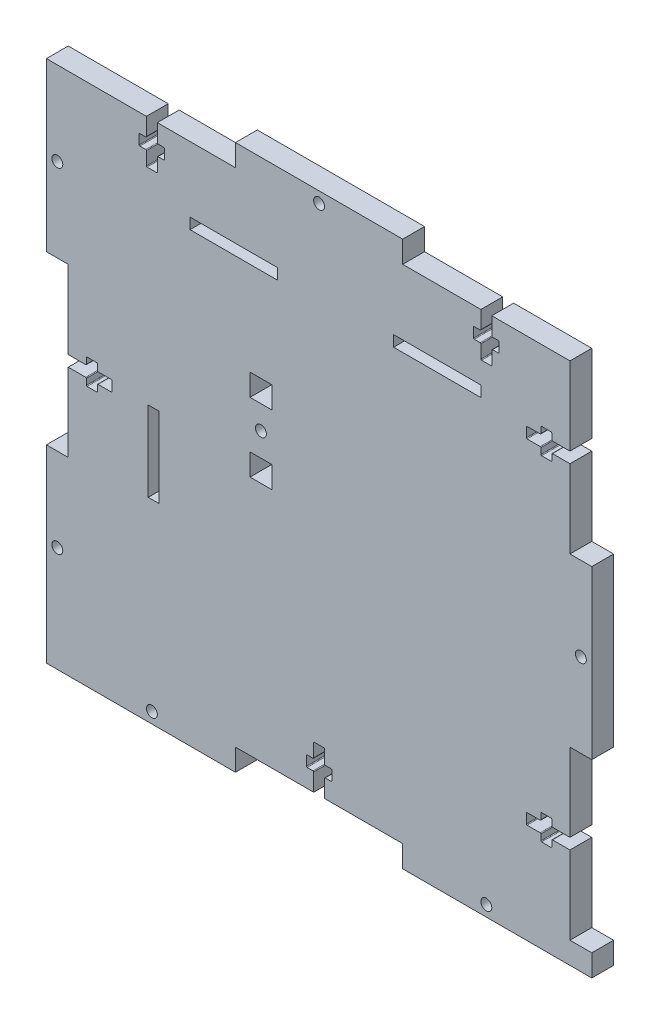
SolidWorks part; units mm, degrees
ref_plane "Front Plane" through (0, 0, 0) normal (0, 0, 1) x (1, 0, 0)
ref_plane "Top Plane" through (0, 0, 0) normal (0, 1, 0) x (1, 0, 0)
ref_plane "Right Plane" through (0, 0, 0) normal (1, 0, 0) x (0, 0, -1)
sketch "Sketch1" plane through (0, 0, 0) normal (0, 0, 1) x (1, 0, 0)
  line L0 (-69, 69) -> (-23, 69)
  line L5 (-75, -75) -> (75, -75) construction
  line L6 (-75, -75) -> (-75, 75) construction
  line L7 (-75, 75) -> (75, 75) construction
  line L8 (75, -75) -> (75, 75) construction
  line L9 (75, 23) -> (69, 23)
  line L10 (69, -23) -> (75, -23)
  line L11 (-69, -69) -> (69, -69) construction
  line L12 (-69, -69) -> (-69, 69) construction
  line L13 (-69, 69) -> (69, 69) construction
  line L14 (69, -69) -> (69, 69) construction
  line L15 (-69, -69) -> (69, 69) construction
  line L16 (69, -69) -> (69, -23)
  line L17 (-23, 69) -> (-23, 75)
  line L18 (-23, 75) -> (23, 75)
  line L19 (23, 75) -> (23, 69)
  line L20 (23, 69) -> (69, 69)
  line L21 (75, -23) -> (75, 23)
  line L22 (69, 23) -> (69, 69)
  line L23 (-75, 23) -> (-69, 23)
  line L24 (-69, 69) -> (-75, 69)
  line L25 (-75, 69) -> (-75, 23)
  line L26 (69, -69) -> (69, -75)
  line L27 (69, -75) -> (23, -75)
  line L28 (23, -75) -> (23, -69)
  line L29 (23, -69) -> (-23, -69)
  line L30 (-23, -69) -> (-23, -75)
  line L31 (-23, -75) -> (-69, -75)
  line L32 (-69, -75) -> (-69, -69) construction
  line L33 (-69, 23) -> (-69, -23)
  line L34 (-69, -23) -> (-75, -23)
  line L35 (-75, -23) -> (-75, -69)
  line L36 (-75, -69) -> (-69, -69) construction
  line L37 (-46, 69) -> (-46, -75) construction
  line L38 (-69, 69) -> (69, -69) construction
  line L39 (-75, -75) -> (-69, -75)
  line L40 (-75, -75) -> (-75, -69)
  point P0 (0, 0)
  point P6 (-7, -7)
  point P26 (0, -75)
  point P27 (-75, 0)
  dimension "D1" = 150
  dimension "D2" = 150
  dimension "D5" = 46
  dimension "D3" = 6
  dimension "D6" = 6
  dimension "D7" = 6
extrude "Box Side" add sketch "Sketch1" along normal blind 6
sketch "Sketch2" plane through (0, 0, 6) normal (0, 0, 1) x (1, 0, 0)
  line L0 (23, 72) -> (-23, 72) construction
  line L1 (23, 75) -> (23, 69) construction
  line L2 (-23, 69) -> (-23, 75) construction
  line L3 (-46, 69) -> (-46, -75) construction
  line L5 (0, 75) -> (0, 69) construction
  line L6 (-23, 75) -> (23, 75) construction
  line L7 (-69, 69) -> (69, 69) construction
  line L16 (-46, 69) -> (-46, -75) construction
  line L21 (0, -69) -> (0, 69) construction
  line L35 (-69, 69) -> (-23, 69) construction
  line L36 (-44.5, 69) -> (-44.5, 64.2)
  line L37 (-44.3, 64) -> (-42.7, 64)
  line L38 (-42.5, 63.8) -> (-42.5, 61.2)
  line L39 (-42.7, 61) -> (-44.3, 61)
  line L40 (-44.5, 60.8) -> (-44.5, 57.2)
  line L46 (-44.7, 57) -> (-47.3, 57)
  line L48 (-44.5, 69) -> (-47.5, 69)
  line L51 (-47.5, 60.8) -> (-47.5, 57.2)
  line L52 (-49.3, 61) -> (-47.7, 61)
  line L53 (-49.5, 63.8) -> (-49.5, 61.2)
  line L54 (-47.7, 64) -> (-49.3, 64)
  line L55 (-47.5, 69) -> (-47.5, 64.2)
  line L56 (47.5, 69) -> (47.5, 64.2)
  line L57 (47.7, 64) -> (49.3, 64)
  line L58 (49.5, 63.8) -> (49.5, 61.2)
  line L59 (49.3, 61) -> (47.7, 61)
  line L60 (47.5, 60.8) -> (47.5, 57.2)
  line L61 (44.5, 69) -> (47.5, 69)
  line L62 (44.7, 57) -> (47.3, 57)
  line L63 (44.5, 60.8) -> (44.5, 57.2)
  line L64 (42.7, 61) -> (44.3, 61)
  line L65 (42.5, 63.8) -> (42.5, 61.2)
  line L66 (44.3, 64) -> (42.7, 64)
  line L67 (44.5, 69) -> (44.5, 64.2)
  line L68 (-69, -69) -> (69, 69) construction
  line L69 (-69, -69) -> (69, 69) construction
  line L70 (75, 0) -> (69, 0) construction
  line L71 (72, 23) -> (72, -23) construction
  line L72 (69, 44.5) -> (64.2, 44.5)
  line L73 (64, 44.3) -> (64, 42.7)
  line L74 (63.8, 42.5) -> (61.2, 42.5)
  line L75 (61, 42.7) -> (61, 44.3)
  line L76 (60.8, 44.5) -> (57.2, 44.5)
  line L77 (57, 44.7) -> (57, 47.3)
  line L78 (69, 44.5) -> (69, 47.5)
  line L79 (60.8, 47.5) -> (57.2, 47.5)
  line L80 (61, 49.3) -> (61, 47.7)
  line L81 (63.8, 49.5) -> (61.2, 49.5)
  line L82 (64, 47.7) -> (64, 49.3)
  line L83 (69, 47.5) -> (64.2, 47.5)
  line L84 (69, -47.5) -> (64.2, -47.5)
  line L85 (64, -47.7) -> (64, -49.3)
  line L86 (63.8, -49.5) -> (61.2, -49.5)
  line L87 (61, -49.3) -> (61, -47.7)
  line L88 (60.8, -47.5) -> (57.2, -47.5)
  line L89 (69, -44.5) -> (69, -47.5)
  line L90 (57, -44.7) -> (57, -47.3)
  line L91 (60.8, -44.5) -> (57.2, -44.5)
  line L92 (61, -42.7) -> (61, -44.3)
  line L93 (63.8, -42.5) -> (61.2, -42.5)
  line L94 (64, -44.3) -> (64, -42.7)
  line L95 (69, -44.5) -> (64.2, -44.5)
  line L120 (-69, 69) -> (69, -69) construction
  line L121 (-69, 69) -> (69, -69) construction
  line L122 (-1.5, -69) -> (1.5, -69)
  line L123 (-23, -69) -> (23, -69) construction
  line L124 (1.5, -69) -> (1.5, -64.2)
  line L125 (1.7, -64) -> (3.3, -64)
  line L126 (3.5, -63.8) -> (3.5, -61.2)
  line L127 (3.3, -61) -> (1.7, -61)
  line L128 (1.5, -60.8) -> (1.5, -57.2)
  line L129 (1.3, -57) -> (-1.3, -57)
  line L130 (-1.5, -60.8) -> (-1.5, -57.2)
  line L131 (-3.3, -61) -> (-1.7, -61)
  line L132 (-3.5, -63.8) -> (-3.5, -61.2)
  line L133 (-1.7, -64) -> (-3.3, -64)
  line L134 (-1.5, -69) -> (-1.5, -64.2)
  line L135 (-69, -1.5) -> (-64.2, -1.5)
  line L136 (-64, -1.7) -> (-64, -3.3)
  line L137 (-63.8, -3.5) -> (-61.2, -3.5)
  line L138 (-61, -3.3) -> (-61, -1.7)
  line L139 (-60.8, -1.5) -> (-57.2, -1.5)
  line L140 (-57, 1.3) -> (-57, -1.3)
  line L141 (-60.8, 1.5) -> (-57.2, 1.5)
  line L142 (-61, 3.3) -> (-61, 1.7)
  line L143 (-63.8, 3.5) -> (-61.2, 3.5)
  line L144 (-64, 1.7) -> (-64, 3.3)
  line L145 (-69, 1.5) -> (-64.2, 1.5)
  line L146 (-69, -1.5) -> (-69, 1.5)
  line L147 (-69, -72) -> (-23, -72) construction
  line L148 (-23, 69) -> (-75, 69) construction
  line L149 (-23, -75) -> (-23, -69) construction
  line L150 (-69, -69) -> (-69, -75) construction
  line L151 (-75, -75) -> (-23, -75) construction
  circle A0 centre (0, 72) radius 1.5
  arc A1 (-44.5, 57.2) -> (-44.7, 57) centre (-44.7, 57.2) cw
  arc A2 (-44.3, 61) -> (-44.5, 60.8) centre (-44.3, 60.8) ccw
  arc A3 (-42.5, 61.2) -> (-42.7, 61) centre (-42.7, 61.2) cw
  arc A4 (-42.7, 64) -> (-42.5, 63.8) centre (-42.7, 63.8) cw
  arc A5 (-44.5, 64.2) -> (-44.3, 64) centre (-44.3, 64.2) ccw
  arc A6 (-47.5, 64.2) -> (-47.7, 64) centre (-47.7, 64.2) cw
  arc A7 (-49.3, 64) -> (-49.5, 63.8) centre (-49.3, 63.8) ccw
  arc A8 (-49.5, 61.2) -> (-49.3, 61) centre (-49.3, 61.2) ccw
  arc A9 (-47.7, 61) -> (-47.5, 60.8) centre (-47.7, 60.8) cw
  arc A10 (-47.5, 57.2) -> (-47.3, 57) centre (-47.3, 57.2) ccw
  arc A11 (47.5, 57.2) -> (47.3, 57) centre (47.3, 57.2) cw
  arc A12 (47.7, 61) -> (47.5, 60.8) centre (47.7, 60.8) ccw
  arc A13 (49.5, 61.2) -> (49.3, 61) centre (49.3, 61.2) cw
  arc A14 (49.3, 64) -> (49.5, 63.8) centre (49.3, 63.8) cw
  arc A15 (47.5, 64.2) -> (47.7, 64) centre (47.7, 64.2) ccw
  arc A16 (44.5, 64.2) -> (44.3, 64) centre (44.3, 64.2) cw
  arc A17 (42.7, 64) -> (42.5, 63.8) centre (42.7, 63.8) ccw
  arc A18 (42.5, 61.2) -> (42.7, 61) centre (42.7, 61.2) ccw
  arc A19 (44.3, 61) -> (44.5, 60.8) centre (44.3, 60.8) cw
  arc A20 (44.5, 57.2) -> (44.7, 57) centre (44.7, 57.2) ccw
  arc A21 (57.2, 44.5) -> (57, 44.7) centre (57.2, 44.7) cw
  arc A22 (61, 44.3) -> (60.8, 44.5) centre (60.8, 44.3) ccw
  arc A23 (61.2, 42.5) -> (61, 42.7) centre (61.2, 42.7) cw
  arc A24 (64, 42.7) -> (63.8, 42.5) centre (63.8, 42.7) cw
  arc A25 (64.2, 44.5) -> (64, 44.3) centre (64.2, 44.3) ccw
  arc A26 (64.2, 47.5) -> (64, 47.7) centre (64.2, 47.7) cw
  arc A27 (64, 49.3) -> (63.8, 49.5) centre (63.8, 49.3) ccw
  arc A28 (61.2, 49.5) -> (61, 49.3) centre (61.2, 49.3) ccw
  arc A29 (61, 47.7) -> (60.8, 47.5) centre (60.8, 47.7) cw
  arc A30 (57.2, 47.5) -> (57, 47.3) centre (57.2, 47.3) ccw
  arc A31 (57.2, -47.5) -> (57, -47.3) centre (57.2, -47.3) cw
  arc A32 (61, -47.7) -> (60.8, -47.5) centre (60.8, -47.7) ccw
  arc A33 (61.2, -49.5) -> (61, -49.3) centre (61.2, -49.3) cw
  arc A34 (64, -49.3) -> (63.8, -49.5) centre (63.8, -49.3) cw
  arc A35 (64.2, -47.5) -> (64, -47.7) centre (64.2, -47.7) ccw
  arc A36 (64.2, -44.5) -> (64, -44.3) centre (64.2, -44.3) cw
  arc A37 (64, -42.7) -> (63.8, -42.5) centre (63.8, -42.7) ccw
  arc A38 (61.2, -42.5) -> (61, -42.7) centre (61.2, -42.7) ccw
  arc A39 (61, -44.3) -> (60.8, -44.5) centre (60.8, -44.3) cw
  arc A40 (57.2, -44.5) -> (57, -44.7) centre (57.2, -44.7) ccw
  circle A41 centre (72, 0) radius 1.5
  arc A62 (1.5, -57.2) -> (1.3, -57) centre (1.3, -57.2) ccw
  arc A63 (1.7, -61) -> (1.5, -60.8) centre (1.7, -60.8) cw
  arc A64 (3.5, -61.2) -> (3.3, -61) centre (3.3, -61.2) ccw
  arc A65 (3.3, -64) -> (3.5, -63.8) centre (3.3, -63.8) ccw
  arc A66 (1.5, -64.2) -> (1.7, -64) centre (1.7, -64.2) cw
  arc A67 (-1.5, -64.2) -> (-1.7, -64) centre (-1.7, -64.2) ccw
  arc A68 (-3.3, -64) -> (-3.5, -63.8) centre (-3.3, -63.8) cw
  arc A69 (-3.5, -61.2) -> (-3.3, -61) centre (-3.3, -61.2) cw
  arc A70 (-1.7, -61) -> (-1.5, -60.8) centre (-1.7, -60.8) ccw
  arc A71 (-1.5, -57.2) -> (-1.3, -57) centre (-1.3, -57.2) cw
  arc A72 (-57.2, -1.5) -> (-57, -1.3) centre (-57.2, -1.3) ccw
  arc A73 (-61, -1.7) -> (-60.8, -1.5) centre (-60.8, -1.7) cw
  arc A74 (-61.2, -3.5) -> (-61, -3.3) centre (-61.2, -3.3) ccw
  arc A75 (-64, -3.3) -> (-63.8, -3.5) centre (-63.8, -3.3) ccw
  arc A76 (-64.2, -1.5) -> (-64, -1.7) centre (-64.2, -1.7) cw
  arc A77 (-64.2, 1.5) -> (-64, 1.7) centre (-64.2, 1.7) ccw
  arc A78 (-64, 3.3) -> (-63.8, 3.5) centre (-63.8, 3.3) cw
  arc A79 (-61.2, 3.5) -> (-61, 3.3) centre (-61.2, 3.3) cw
  arc A80 (-61, 1.7) -> (-60.8, 1.5) centre (-60.8, 1.7) ccw
  arc A81 (-57.2, 1.5) -> (-57, 1.3) centre (-57.2, 1.3) cw
  circle A82 centre (-46, -72) radius 1.5
  circle A83 centre (46, -72) radius 1.5
  circle A84 centre (-72, 46) radius 1.5
  circle A85 centre (-72, -46) radius 1.5
  point P6 (0, 72)
  point P38 (0, 0)
  point P56 (-46, 57)
  point P88 (46, 57)
  point P161 (57, 46)
  point P162 (57, -46)
  point P198 (0, -57)
  point P231 (-57, 0)
  point P234 (-42.5, 62.5)
  dimension "D1" = 3
  dimension "D2" = 0.2
  dimension "D8" = 0.2
  dimension "D14" = 3
  dimension "D4" = 3
  dimension "D7" = 1.5
  dimension "D10" = 3
  dimension "D12" = 1.5
  dimension "D9" = 12
  dimension "D11" = 5
  dimension "D13" = 7
  dimension "D3" = 12
  dimension "D5" = 7
  dimension "D6" = 5
extrude "Screw Cut-outs" cut sketch "Sketch2" against normal through all
sketch "Sketch3" plane through (0, 0, 6) normal (0, 0, 1) x (1, 0, 0)
  line L0 (69, 23) -> (69, 44.5) construction
  line L1 (44.5, 51) -> (20.5, 51)
  line L2 (44.5, 51) -> (44.5, 48)
  line L3 (44.5, 48) -> (20.5, 48)
  line L4 (20.5, 51) -> (20.5, 48)
  line L5 (44.5, 69) -> (23, 69) construction
  line L6 (75, -23) -> (75, 23) construction
  line L7 (-13, 22.32) -> (-19, 22.32)
  line L8 (-13, 22.32) -> (-13, 16.32)
  line L9 (-13, 16.32) -> (-19, 16.32)
  line L10 (-19, 22.32) -> (-19, 16.32)
  line L11 (-13, 3.32) -> (-19, 3.32)
  line L12 (-13, 3.32) -> (-13, -2.68)
  line L13 (-13, -2.68) -> (-19, -2.68)
  line L14 (-19, 3.32) -> (-19, -2.68)
  line L15 (-23, -69) -> (-1.5, -69) construction
  line L16 (-16, 3.32) -> (-16, 16.32) construction
  line L17 (-75, -23) -> (-75, -75) construction
  line L18 (-11.5, 51) -> (-35.5, 51)
  line L19 (-11.5, 51) -> (-11.5, 48)
  line L20 (-11.5, 48) -> (-35.5, 48)
  line L21 (-35.5, 51) -> (-35.5, 48)
  line L22 (-44, 0.5) -> (-47, 0.5)
  line L23 (-44, 0.5) -> (-44, -21.5)
  line L24 (-44, -21.5) -> (-47, -21.5)
  line L25 (-47, 0.5) -> (-47, -21.5)
  line L26 (-75, -75) -> (-23, -75) construction
  circle A0 centre (-16, 9.82) radius 1.5
  point P22 (-16, 16.32)
  point P27 (-16, 9.82)
  dimension "D9" = 3
  dimension "D1" = 3
  dimension "D2" = 24.5
  dimension "D3" = 24
  dimension "D4" = 18
  dimension "D5" = 6
  dimension "D6" = 88
  dimension "D7" = 66.32
  dimension "D8" = 13
  dimension "D10" = 32
  dimension "D11" = 22
  dimension "D12" = 3
  dimension "D13" = 28
  dimension "D14" = 53.5
extrude "Grooves" cut sketch "Sketch3" against normal through all
sketch "Sketch4" plane through (0, 0, 0) normal (0, 0, -1) x (-1, 0, 0)
  line L1 (-69, -75) -> (-75, -75)
  line L2 (-69, -75) -> (-69, -69)
  line L3 (-69, -69) -> (-75, -69)
  line L4 (-75, -75) -> (-75, -69)
  dimension "D1" = 6
  dimension "D2" = 6
extrude "Boss-Extrude1" add sketch "Sketch4" against normal blind 6
equation "\"filletRadius\"=0.2"
equation "\"D8@Sketch2\"=\"filletRadius\""
equation "\"D2@Sketch2\"=\"filletRadius\""
equation "\"fingerWidth\"= 46"
equation "\"D5@Sketch1\"=\"fingerWidth\""
equation "\"wallThickness\"= 6"
equation "\"D3@Sketch1\" = \"wallThickness\""
equation "\"D6@Sketch1\" = \"wallThickness\""
equation "\"D7@Sketch1\" = \"wallThickness\""
equation "\"D1@Box Side\" = \"wallThickness\""
equation "\"M3\"= 3"
equation "\"D14@Sketch2\"=\"M3\""
equation "\"D1@Sketch2\"=\"M3\""
equation "\"D12@Sketch2\"=\"M3\"/2"
equation "\"nutThickness\"=3"
equation "\"D10@Sketch2\" = \"nutThickness\""
equation "\"boltLength\"= 12"
equation "\"D9@Sketch2\" = \"boltLength\""
equation "\"distanceToNut\"= 5"
equation "\"D11@Sketch2\" = \"distanceToNut\""
equation "\"D13@Sketch2\" = \"nutWidth\""
equation "\"D7@Sketch2\"=\"M3\"/2"
equation "\"D4@Sketch2\" = \"nutThickness\""
equation "\"D3@Sketch2\" = \"boltLength\""
equation "\"D5@Sketch2\" = \"nutWidth\""
equation "\"D6@Sketch2\" = \"distanceToNut\""
equation "\"sideLength\"=150"
equation "\"D1@Sketch1\"=\"sideLength\""
equation "\"D2@Sketch1\"=\"sideLength\""
equation "\"nutWidth\"=7"
